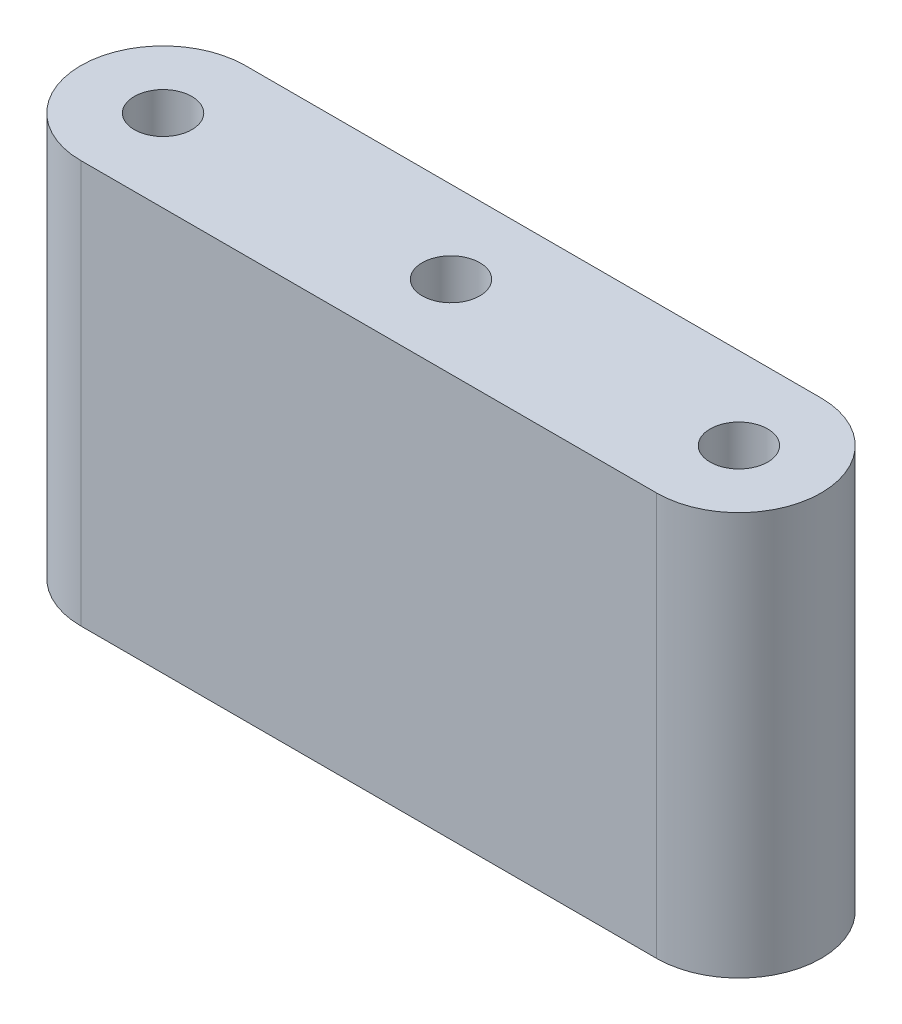
SolidWorks part; units mm, degrees
ref_plane "Front Plane" through (0, 0, 0) normal (0, 0, 1) x (1, 0, 0)
ref_plane "Top Plane" through (0, 0, 0) normal (0, 1, 0) x (1, 0, 0)
ref_plane "Right Plane" through (0, 0, 0) normal (1, 0, 0) x (0, 0, -1)
sketch "Sketch1" plane through (0, 0, 0) normal (0, 1, 0) x (1, 0, 0)
  line L0 (0, 0) -> (35, 0)
  line L1 (0, 0) -> (-35, 0)
  line L2 (-35, 0) -> (35, 0) construction
  line L3 (5.125, -2.9589) -> (5.125, 2.9589) construction
  line L4 (5.125, 2.9589) -> (0, 5.9178) construction
  line L5 (0, 5.9178) -> (-5.125, 2.9589) construction
  line L6 (-5.125, 2.9589) -> (-5.125, -2.9589) construction
  line L7 (-5.125, -2.9589) -> (0, -5.9178) construction
  line L8 (0, -5.9178) -> (5.125, -2.9589) construction
  line L9 (-35, 10) -> (35, 10)
  line L10 (-35, -10) -> (35, -10)
  circle A0 centre (0, 0) radius 5.125 construction
  circle A1 centre (0, 0) radius 6.75
  circle A2 centre (35, 0) radius 6.75
  circle A3 centre (-35, 0) radius 6.75
  arc A4 (-35, 10) -> (-35, -10) centre (-35, 0) ccw
  arc A5 (35, -10) -> (35, 10) centre (35, 0) ccw
  point P14 (0, 0)
  point P20 (0, 0)
  dimension "D3" = 13.5
  dimension "D4" = 20
  dimension "D1" = 35
  dimension "D2" = 10.25
extrude "Boss-Extrude1" add sketch "Sketch1" along normal blind 6
sketch "Sketch2" plane through (0, 6, 0) normal (0, 1, 0) x (1, 0, 0)
  line L2 (-35, -10) -> (35, -10)
  line L3 (35, 10) -> (-35, 10)
  line L4 (-35, -10) -> (35, -10)
  line L5 (35, 10) -> (-35, 10)
  circle A0 centre (-35, 0) radius 3.5
  circle A1 centre (0, 0) radius 3.5
  arc A2 (35, -10) -> (35, 10) centre (35, 0) ccw
  arc A3 (-35, 10) -> (-35, -10) centre (-35, 0) ccw
  arc A4 (35, -10) -> (35, 10) centre (35, 0) ccw
  arc A5 (-35, 10) -> (-35, -10) centre (-35, 0) ccw
  circle A6 centre (35, 0) radius 3.5
  dimension "D2" = 7
  dimension "D1" = 0
extrude "Boss-Extrude2" add sketch "Sketch2" along normal blind 43
